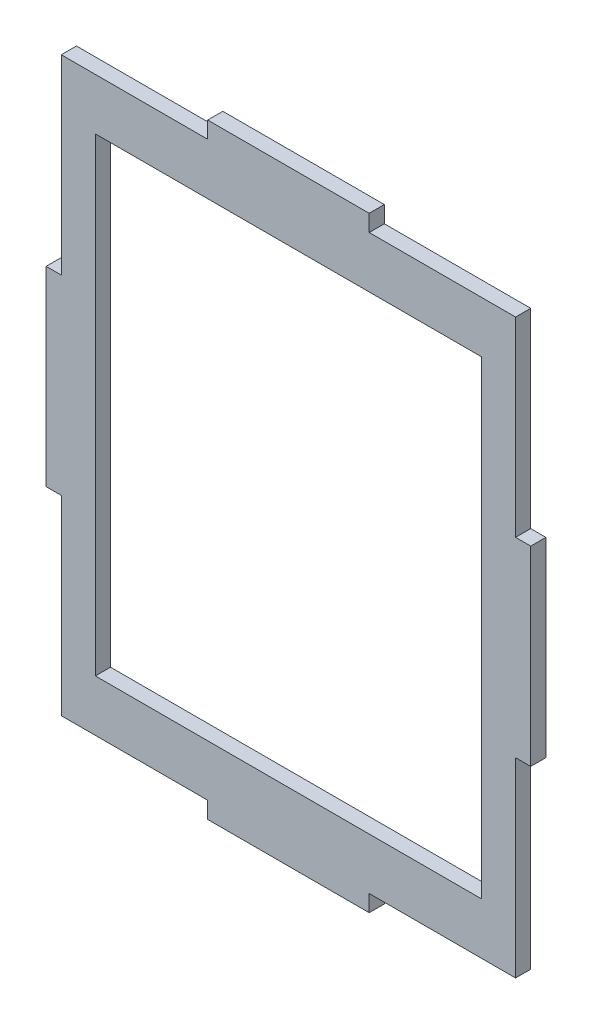
SolidWorks part; units mm, degrees
ref_plane "Front Plane" through (0, 0, 0) normal (0, 0, 1) x (1, 0, 0)
ref_plane "Top Plane" through (0, 0, 0) normal (0, 1, 0) x (1, 0, 0)
ref_plane "Right Plane" through (0, 0, 0) normal (1, 0, 0) x (0, 0, -1)
sketch "Sketch1" plane through (0, 0, 0) normal (0, 0, 1) x (1, 0, 0)
  line L1 (40.64, 50.8) -> (-40.64, 50.8)
  line L2 (40.64, 50.8) -> (40.64, -50.8)
  line L3 (40.64, -50.8) -> (-40.64, -50.8)
  line L4 (-40.64, 50.8) -> (-40.64, -50.8)
  line L5 (40.64, 50.8) -> (-40.64, -50.8) construction
  line L6 (40.64, -50.8) -> (-40.64, 50.8) construction
  point P0 (0, 0)
  dimension "D1" = 101.6
  dimension "D2" = 81.28
extrude "Boss-Extrude1" add sketch "Sketch1" along normal blind 2.54
sketch "Sketch2" plane through (0, 0, 0) normal (0, 0, -1) x (-1, 0, 0)
  line L0 (40.64, 50.8) -> (40.64, -50.8) construction
  line L1 (-40.64, -50.8) -> (40.64, -50.8)
  line L2 (-40.64, -50.8) -> (-40.64, -48.006)
  line L3 (40.64, -48.006) -> (13.5467, -48.006)
  line L4 (40.64, -50.8) -> (40.64, -48.006)
  line L5 (-13.5467, -50.8) -> (-13.5467, -48.006)
  line L6 (13.5467, -48.006) -> (-13.5467, -48.006)
  line L7 (13.5467, -50.8) -> (13.5467, -48.006)
  line L10 (-13.5467, -48.006) -> (-40.64, -48.006)
  line L11 (-40.64, -48.006) -> (-40.617, -44.1703)
  line L12 (0, 0) -> (47.9226, 0) construction
  line L13 (-40.64, 48.006) -> (-40.617, 44.1703)
  line L14 (-13.5467, 48.006) -> (-40.64, 48.006)
  line L15 (13.5467, 48.006) -> (-13.5467, 48.006)
  line L17 (13.5467, 50.8) -> (13.5467, 48.006)
  line L19 (-13.5467, 50.8) -> (-13.5467, 48.006)
  line L20 (40.64, 50.8) -> (40.64, 48.006)
  line L21 (40.64, 48.006) -> (13.5467, 48.006)
  line L22 (-40.64, 50.8) -> (-40.64, 48.006)
  line L23 (-40.64, 50.8) -> (40.64, 50.8)
  line M1 (40.64, -50.8) -> (40.64, 50.8)
  line M2 (40.64, 50.8) -> (-40.64, 50.8)
  line M3 (-40.64, 50.8) -> (-40.64, -50.8)
  line M4 (-40.64, -50.8) -> (40.64, -50.8)
  dimension "D1" = 2.794
extrude "Cut-Extrude4" cut sketch "Sketch2" against normal through all contours L7 L3 M4 M1 | L5 L10 M3 M4 | L19 L14 M2 M3 | L21 L17 M1 M2
sketch "Sketch8" plane through (0, 0, 2.54) normal (0, 0, 1) x (1, 0, 0)
  line L0 (-40.64, -48.006) -> (-13.5467, -48.006) construction
  line L1 (-40.64, 48.006) -> (-38.1, 48.006)
  line L2 (-40.64, 48.006) -> (-40.64, -48.006)
  line L3 (-40.64, -48.006) -> (-38.1, -48.006)
  line L4 (-38.1, 16.002) -> (-38.1, 48.006)
  line L6 (0, 50.8) -> (0, -50.8) construction
  line L7 (13.5467, 50.8) -> (-13.5467, 50.8) construction
  line L8 (-13.5467, -50.8) -> (13.5467, -50.8) construction
  line L9 (38.1, -16.002) -> (38.1, -48.006)
  line L10 (-38.1, 16.002) -> (-40.64, 16.002)
  line L11 (-38.1, -16.002) -> (-40.64, -16.002)
  line L12 (-38.1, 16.002) -> (-38.1, -16.002)
  line L13 (-38.1, -16.002) -> (-38.1, -48.006)
  line L14 (38.1, 16.002) -> (38.1, -16.002)
  line L15 (38.1, -16.002) -> (40.64, -16.002)
  line L16 (38.1, 16.002) -> (40.64, 16.002)
  line L17 (38.1, 16.002) -> (38.1, 48.006)
  line L18 (40.64, -48.006) -> (38.1, -48.006)
  line L19 (40.64, 48.006) -> (40.64, -48.006)
  line L20 (40.64, 48.006) -> (38.1, 48.006)
  dimension "D1" = 2.54
extrude "Cut-Extrude9" cut sketch "Sketch8" against normal through all contours L13 L11 L2 L3 | L10 L4 L1 L2 | L19 L20 L17 L16 | L19 L15 L9 L18
sketch "Sketch9" plane through (0, 0, 2.54) normal (0, 0, 1) x (1, 0, 0)
  line L1 (32.385, 39.37) -> (-32.385, 39.37)
  line L2 (32.385, 39.37) -> (32.385, -39.37)
  line L3 (32.385, -39.37) -> (-32.385, -39.37)
  line L4 (-32.385, 39.37) -> (-32.385, -39.37)
  line L5 (32.385, 39.37) -> (-32.385, -39.37) construction
  line L6 (32.385, -39.37) -> (-32.385, 39.37) construction
  point P0 (0, 0)
  dimension "D1" = 78.74
  dimension "D2" = 64.77
extrude "Cut-Extrude10" cut sketch "Sketch9" against normal through all
